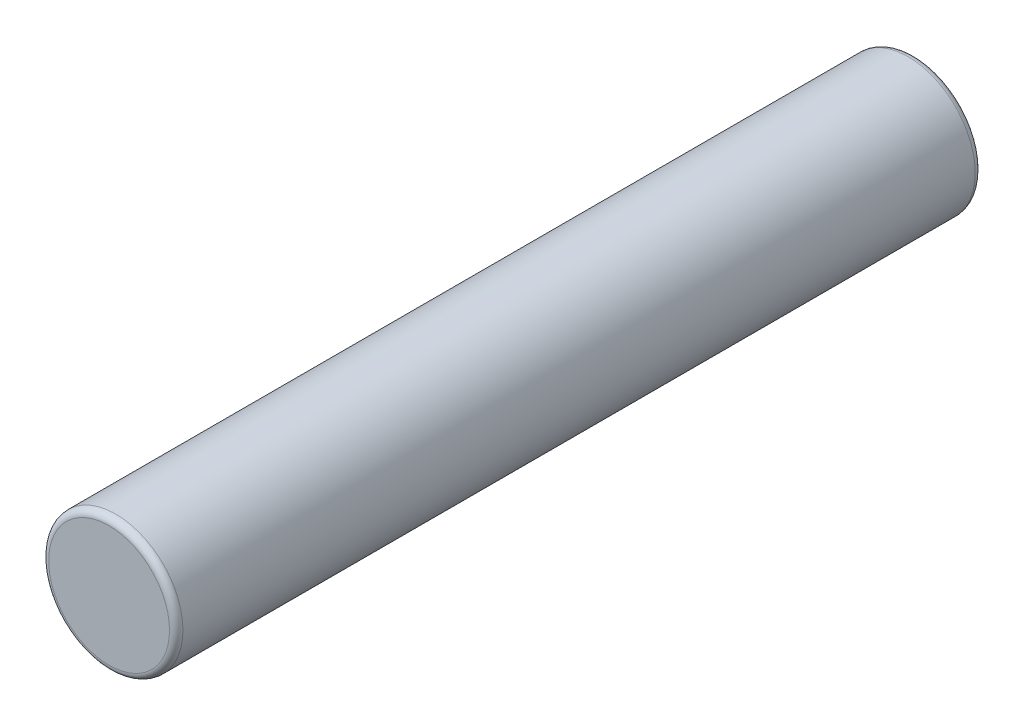
SolidWorks part; units mm, degrees
ref_plane "Front Plane" through (0, 0, 0) normal (0, 0, 1) x (1, 0, 0)
ref_plane "Top Plane" through (0, 0, 0) normal (0, 1, 0) x (1, 0, 0)
ref_plane "Right Plane" through (0, 0, 0) normal (1, 0, 0) x (0, 0, -1)
sketch "Sketch1" plane through (0, 0, 0) normal (0, 0, 1) x (1, 0, 0)
  circle A0 centre (0, 0) radius 1
  dimension "D1" = 2
extrude "Extrude1" add sketch "Sketch1" along normal blind 12
fillet "Fillet1" radius 0.1 2 edges at (1, 0, 0) (1, 0, 12)
